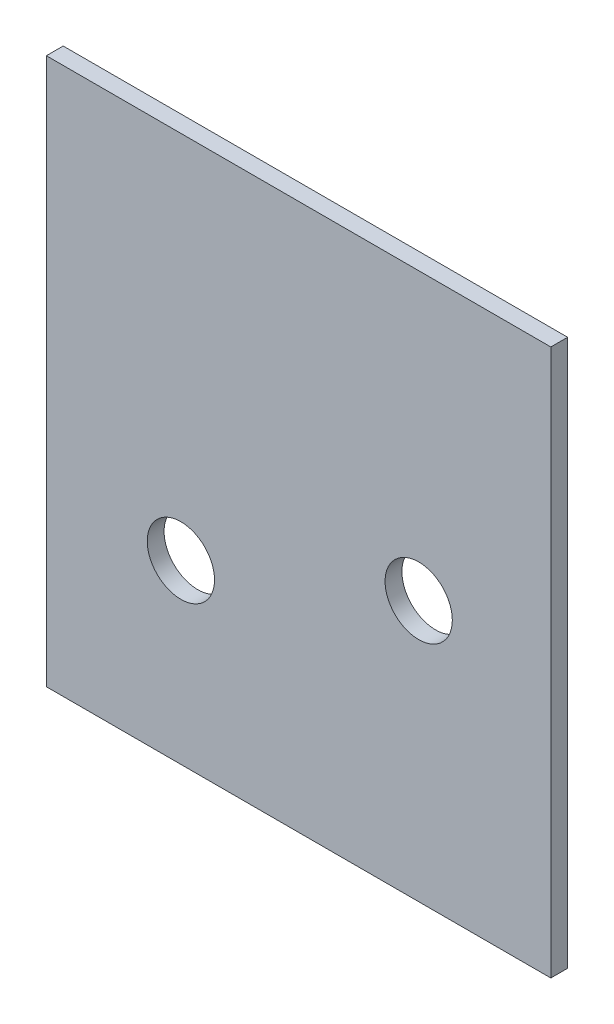
SolidWorks part; units mm, degrees
ref_plane "前视基准面" through (0, 0, 0) normal (0, 0, 1) x (1, 0, 0)
ref_plane "上视基准面" through (0, 0, 0) normal (0, 1, 0) x (1, 0, 0)
ref_plane "右视基准面" through (0, 0, 0) normal (1, 0, 0) x (0, 0, -1)
other "Configuration Table"
sketch "草图1" plane through (0, 0, 0) normal (0, 0, 1) x (1, 0, 0)
  line L1 (-150, -150) -> (150, -150)
  line L2 (-150, -150) -> (-150, 150)
  line L3 (-150, 150) -> (150, 150)
  line L4 (150, -150) -> (150, 150)
  line L5 (-150, -150) -> (150, 150) construction
  line L6 (-150, 150) -> (150, -150) construction
  point P0 (0, 0)
  dimension "D1" = 300
  dimension "D2" = 300
extrude "凸台-拉伸1" add sketch "草图1" along normal blind 10
sketch "草图2" plane through (0, 0, 10) normal (0, 0, 1) x (1, 0, 0)
  line L0 (-150, 150) -> (-150, -150) construction
  line L1 (-150, -150) -> (150, -150) construction
  circle A0 centre (-70, -70) radius 20
  circle A1 centre (71.4214, -20) radius 20
  dimension "D3" = 40
  dimension "D4" = 40
  dimension "D1" = 80
  dimension "D2" = 80
  dimension "D5" = 150
  dimension "D6" = 50
extrude "切除-拉伸1" cut sketch "草图2" against normal through all
sketch "草图3" plane through (0, -150, 0) normal (0, -1, 0) x (1, 0, 0)
  line L4 (-150, 0) -> (150, 0)
  line L5 (150, 0) -> (150, 10)
  line L6 (150, 10) -> (-150, 10)
  line L7 (-150, 10) -> (-150, 0)
  line L8 (-150, 0) -> (150, 0)
  line L9 (150, 0) -> (150, 10)
  line L10 (150, 10) -> (-150, 10)
  line L11 (-150, 10) -> (-150, 0)
  dimension "D1" = 0
extrude "凸台-拉伸2" add sketch "草图3" along normal blind 25
